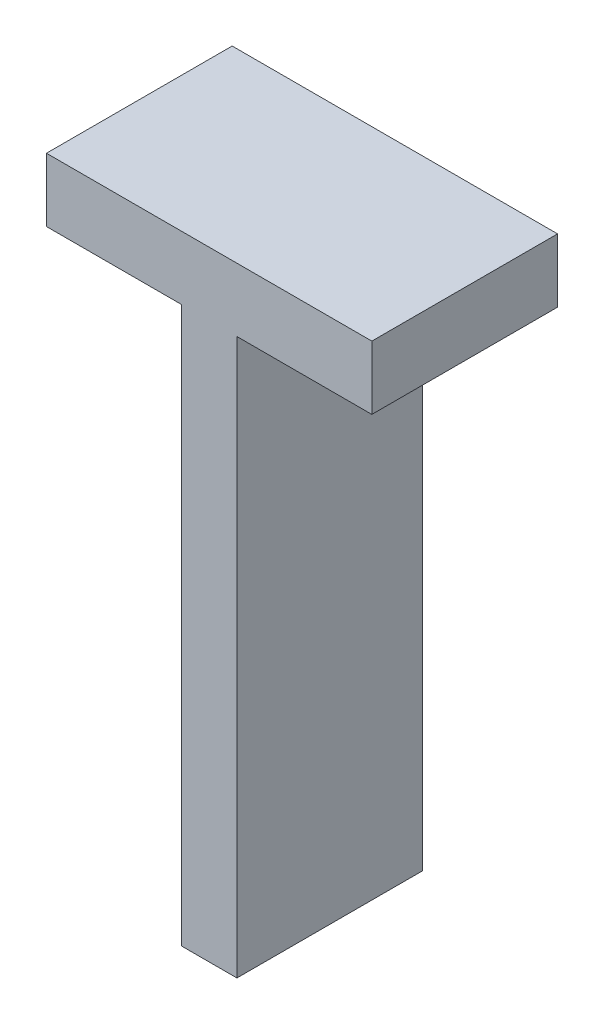
SolidWorks part; units mm, degrees
ref_plane "Plan de face" through (0, 0, 0) normal (0, 0, 1) x (1, 0, 0)
ref_plane "Plan de dessus" through (0, 0, 0) normal (0, 1, 0) x (1, 0, 0)
ref_plane "Plan de droite" through (0, 0, 0) normal (1, 0, 0) x (0, 0, -1)
sketch "Esquisse1" plane through (0, 0, 0) normal (0, 0, 1) x (1, 0, 0)
  text T0 "T" font "Century Gothic" height 5
extrude "Boss.-Extru.1" add sketch "Esquisse1" along normal blind 1.5
